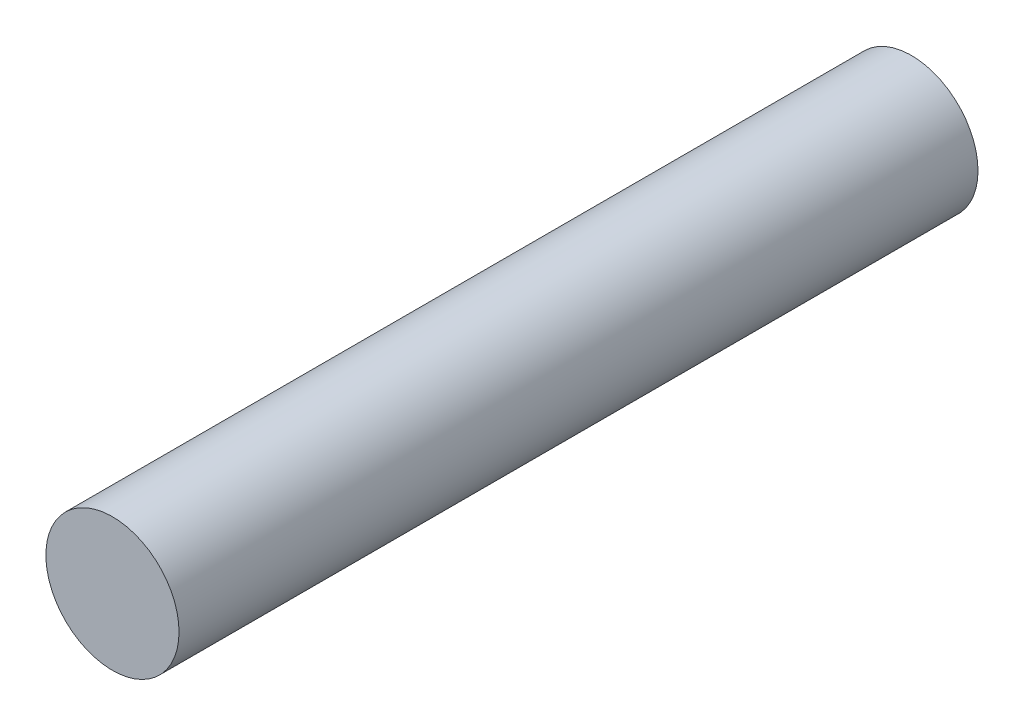
SolidWorks part; units mm, degrees
ref_plane "Front Plane" through (0, 0, 0) normal (0, 0, 1) x (1, 0, 0)
ref_plane "Top Plane" through (0, 0, 0) normal (0, 1, 0) x (1, 0, 0)
ref_plane "Right Plane" through (0, 0, 0) normal (1, 0, 0) x (0, 0, -1)
sketch "Sketch2" plane through (0, 0, 0) normal (0, 0, 1) x (1, 0, 0)
  circle A0 centre (0, 0) radius 38.1
  dimension "D1" = 76.2
extrude "Boss-Extrude1" add sketch "Sketch2" along normal blind 457.2
